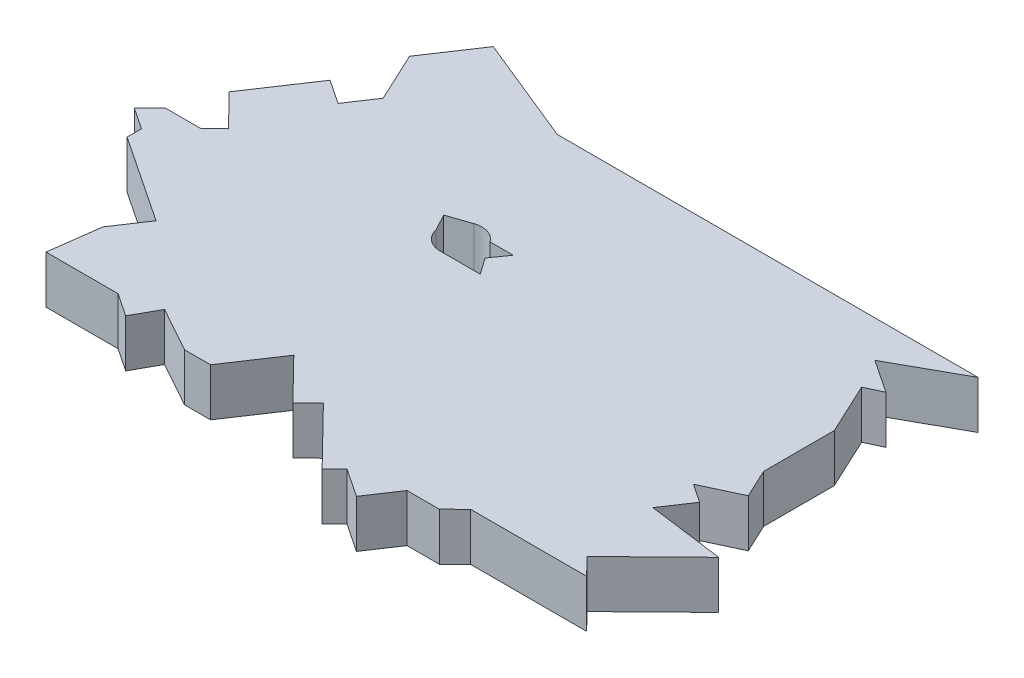
SolidWorks part; units mm, degrees
ref_plane "Front Plane" through (0, 0, 0) normal (0, 0, 1) x (1, 0, 0)
ref_plane "Top Plane" through (0, 0, 0) normal (0, 1, 0) x (1, 0, 0)
ref_plane "Right Plane" through (0, 0, 0) normal (1, 0, 0) x (0, 0, -1)
sketch "Sketch1" plane through (0, 0, 0) normal (0, 1, 0) x (1, 0, 0)
  line L0 (-30.7872, 46.0601) -> (67.4242, 46.0601)
  line L1 (67.4242, 46.0601) -> (81.1443, 46.0601)
  line L2 (81.1443, 46.0601) -> (63.5042, 36.2601)
  line L3 (63.5042, 36.2601) -> (72.3242, 30.3801)
  line L4 (72.3242, 30.3801) -> (67.9142, 28.3221)
  line L5 (67.9142, 28.3221) -> (74.2842, 14.672)
  line L6 (74.2842, 14.672) -> (74.2842, 9.604)
  line L7 (74.2842, 9.604) -> (74.2842, -4.116)
  line L8 (74.2842, -4.116) -> (77.8645, -11.7879)
  line L9 (77.8645, -11.7879) -> (67.9142, -16.4314)
  line L10 (67.9142, -16.4314) -> (72.8893, -19.7481)
  line L11 (72.8893, -19.7481) -> (67.9142, -27.2108)
  line L12 (67.9142, -27.2108) -> (88.1249, -29.9052)
  line L13 (88.1249, -29.9052) -> (70.4018, -47.2362)
  line L14 (70.4018, -47.2362) -> (74.9143, -51.8508)
  line L15 (74.9143, -51.8508) -> (44.0703, -51.8508)
  line L16 (4.7636, -51.8508) -> (0, -46.9794)
  line L17 (0, -46.9794) -> (-4.105, -50.9936)
  line L18 (-4.105, -50.9936) -> (-14.9985, -39.8536)
  line L19 (-14.9985, -39.8536) -> (-23.8623, -53.1493)
  line L20 (-23.8623, -53.1493) -> (-30.7872, -53.1493)
  line L21 (-30.7872, -53.1493) -> (-42.7281, -46.5015)
  line L22 (-42.7281, -46.5015) -> (-46.4292, -53.1493)
  line L23 (-46.4292, -53.1493) -> (-52.5666, -49.0578)
  line L24 (-52.5666, -49.0578) -> (-62.3282, -49.0578)
  line L25 (-62.3282, -49.0578) -> (-71.7362, -49.0578)
  line L26 (-71.7362, -49.0578) -> (-69.9551, -35.6976)
  line L27 (-69.9551, -35.6976) -> (-64.2973, -27.2108)
  line L28 (-64.2973, -27.2108) -> (-87.4316, -11.7879)
  line L29 (-87.4316, -11.7879) -> (-87.4316, -7.952)
  line L30 (-87.4316, -7.952) -> (-93.1856, -4.116)
  line L31 (-93.1856, -4.116) -> (-88.9764, 0)
  line L32 (-88.9764, 0) -> (-79.573, 0)
  line L33 (-79.573, 0) -> (-75.8645, 3.6265)
  line L34 (-75.8645, 3.6265) -> (-84.2747, 12.227)
  line L35 (-84.2747, 12.227) -> (-78.0947, 21.4971)
  line L36 (-78.0947, 21.4971) -> (-73.5447, 28.3221)
  line L37 (-73.5447, 28.3221) -> (-67.1262, 24.0431)
  line L38 (-67.1262, 24.0431) -> (-62.3282, 31.2401)
  line L39 (-62.3282, 31.2401) -> (-68.4781, 44.4185)
  line L40 (-68.4781, 44.4185) -> (-59.5709, 57.7793)
  line L41 (-11.9236, 7.9863) -> (-8.8487, 3.6095)
  line L42 (-59.5709, 57.7793) -> (-30.7872, 46.0601)
  line L43 (-8.8487, 3.6095) -> (-19.5467, 3.6095)
  line L44 (4.7636, -51.8508) -> (14.9696, -62.2877)
  line L45 (14.9696, -62.2877) -> (18.3185, -59.0129)
  line L46 (18.3185, -59.0129) -> (25.876, -64.0512)
  line L47 (25.876, -64.0512) -> (31.2511, -55.9885)
  line L48 (31.2511, -55.9885) -> (39.839, -55.9885)
  line L49 (39.839, -55.9885) -> (44.0703, -51.8508)
  line L50 (-14.9985, 12.3632) -> (-8.8487, 12.3632)
  line L51 (-8.8487, 12.3632) -> (-11.9236, 7.9863)
  line L52 (-21.3586, 14.4228) -> (-27.332, 12.3632)
  line L53 (-27.332, 12.3632) -> (-24.9782, 7.9863)
  arc A0 (-14.9985, 12.3632) -> (-21.3586, 14.4228) centre (-19.5467, 9.1679) ccw
  arc A1 (-24.9782, 7.9863) -> (-19.5467, 3.6095) centre (-19.5467, 9.1679) ccw
extrude "Boss-Extrude1" add sketch "Sketch1" along normal blind 12.7
